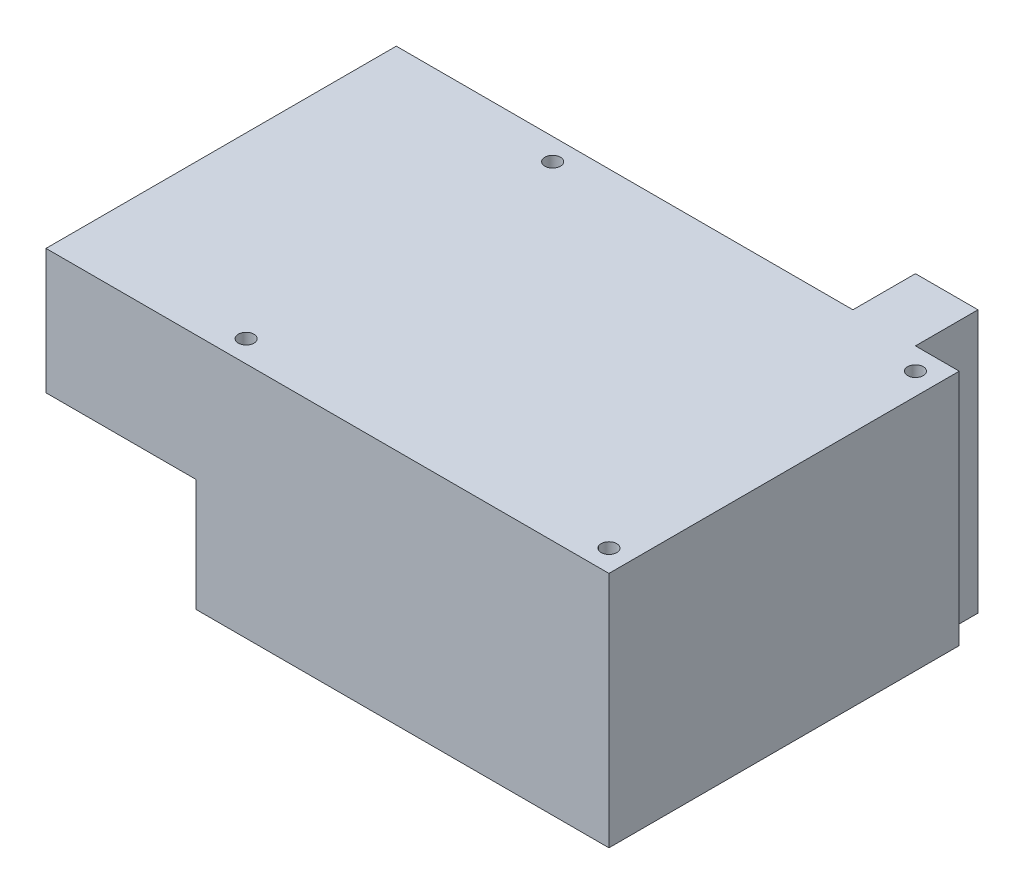
SolidWorks part; units mm, degrees
material "A-玻璃纤维"
ref_plane "前视基准面" through (0, 0, 0) normal (0, 0, 1) x (1, 0, 0)
ref_plane "上视基准面" through (0, 0, 0) normal (0, 1, 0) x (1, 0, 0)
ref_plane "右视基准面" through (0, 0, 0) normal (1, 0, 0) x (0, 0, -1)
other "Configuration Table"
sketch "草图1" plane through (0, 0, 0) normal (0, 1, 0) x (1, 0, 0)
  line L1 (-45, -28) -> (45, -28)
  line L2 (-45, -28) -> (-45, 28)
  line L3 (-45, 28) -> (45, 28)
  line L4 (45, -28) -> (45, 28)
  line L5 (-45, -28) -> (45, 28) construction
  line L6 (-45, 28) -> (45, -28) construction
  point P0 (0, 0)
  dimension "D1" = 90
  dimension "D2" = 56
extrude "凸台-拉伸1" add sketch "草图1" along normal blind 20
sketch "草图4" plane through (0, 0, 0) normal (0, -1, 0) x (1, 0, 0)
  line L0 (45, 28) -> (-21, 28)
  line L1 (-45, 28) -> (45, 28) construction
  line L2 (-21, 28) -> (-21, -28)
  line L3 (45, -28) -> (-45, -28) construction
  line L4 (-21, -28) -> (45, -28)
  line L5 (45, -28) -> (45, 28)
  dimension "D1" = 66
extrude "凸台-拉伸3" add sketch "草图4" along normal blind 18
sketch "草图2" plane through (0, 20, 0) normal (0, 1, 0) x (1, 0, 0)
  line L0 (0, 0) -> (63.2874, 0) construction
  line L1 (45, -28) -> (45, 28) construction
  line L2 (-20, -28) -> (45, -28) construction
  line L3 (-20, -28) -> (-20, 28) construction
  line L4 (-20, 28) -> (45, 28) construction
  line L5 (45, -28) -> (45, 28) construction
  line L6 (-20, -28) -> (45, 28) construction
  line L7 (-20, 28) -> (45, -28) construction
  line L8 (12.5, 0) -> (12.5, 65.7232) construction
  circle A0 centre (41.5, 24.5) radius 1.25
  circle A1 centre (41.5, -24.5) radius 1.25
  circle A2 centre (-16.5, -24.5) radius 1.25
  circle A3 centre (-16.5, 24.5) radius 1.25
  point P3 (12.5, 0)
  dimension "D3" = 2.5
  dimension "D4" = 49
  dimension "D5" = 58
  dimension "D1" = 65
  dimension "D2" = 56
extrude "切除-拉伸1" cut sketch "草图2" against normal blind 60
sketch "草图5" plane through (0, 20, 0) normal (0, 1, 0) x (1, 0, 0)
  line L0 (38, 28) -> (38, 38)
  line L1 (45, 28) -> (-45, 28) construction
  line L2 (38, 38) -> (28, 38)
  line L3 (28, 38) -> (28, 28)
  line L4 (28, 28) -> (38, 28)
  line L5 (45, -28) -> (45, 28) construction
  dimension "D1" = 10
  dimension "D2" = 7
  dimension "D3" = 10
extrude "凸台-拉伸4" add sketch "草图5" against normal blind 42
